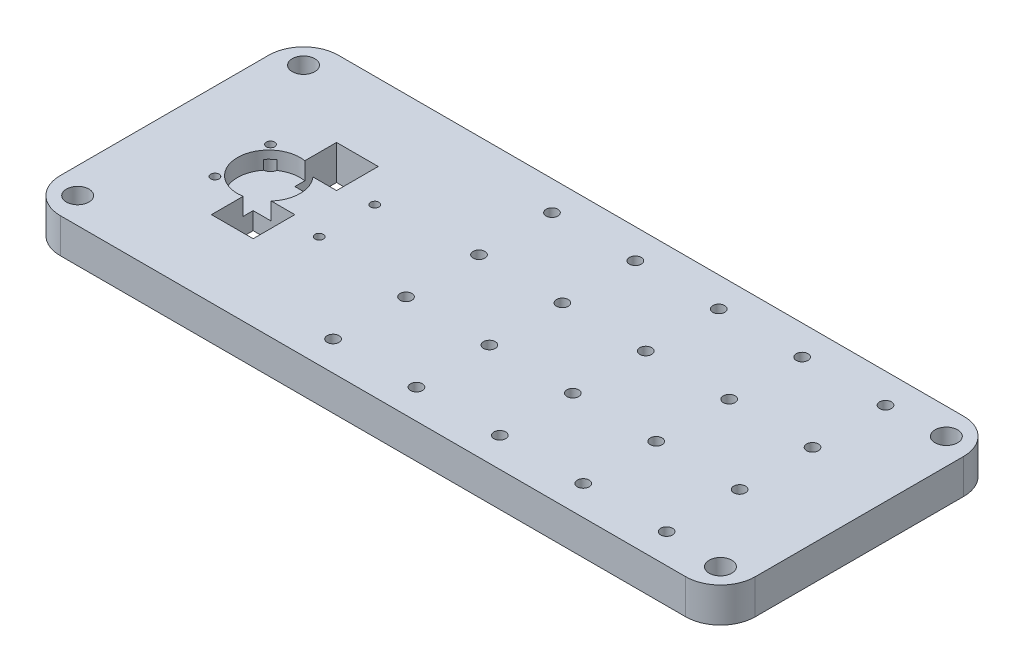
SolidWorks part; units mm, degrees
ref_plane "前视基准面" through (0, 0, 0) normal (0, 0, 1) x (1, 0, 0)
ref_plane "上视基准面" through (0, 0, 0) normal (0, 1, 0) x (1, 0, 0)
ref_plane "右视基准面" through (0, 0, 0) normal (1, 0, 0) x (0, 0, -1)
other "Configuration Table"
sketch "草图1" plane through (0, 0, 0) normal (0, 1, 0) x (1, 0, 0)
  line L1 (-100, 40) -> (100, 40)
  line L2 (-100, 40) -> (-100, -40)
  line L3 (-100, -40) -> (100, -40)
  line L4 (100, 40) -> (100, -40)
  line L5 (-100, 40) -> (100, -40) construction
  line L6 (-100, -40) -> (100, 40) construction
  point P0 (0, 0)
  dimension "D1" = 200
  dimension "D2" = 80
extrude "凸台-拉伸1" add sketch "草图1" along normal blind 10
sketch "草图3" plane through (0, 10, 0) normal (0, 1, 0) x (1, 0, 0)
  circle A0 centre (-70, 0) radius 9
  dimension "D1" = 18
  dimension "D2" = 70
extrude "切除-拉伸1" cut sketch "草图3" against normal blind 5
sketch "草图4" plane through (0, 0, 0) normal (0, -1, 0) x (1, 0, 0)
  line L0 (0, 0) -> (-107.4442, 0) construction
  circle A0 centre (-70, 0) radius 9 construction
  point P3 (-77.5, 8)
  point P4 (-47.5, 8)
  point P5 (-47.5, -8)
  point P6 (-77.5, -8)
  dimension "D3" = 7.5
  dimension "D1" = 30
  dimension "D2" = 16
hole_wizard "M2 六角凹头螺钉的柱形沉头孔1" positions "草图7" profile "草图6" counterbore size "M2" standard "ISO" end condition through all
sketch "草图7" plane through (0, 0, 0) normal (0, -1, 0) x (-1, 0, 0)
  point P0 (47.5, 8)
  point P3 (77.5, 8)
  point P6 (77.5, -8)
  point P9 (47.5, -8)
sketch "草图6" plane through (-47.5, 0, -8) normal (1, 0, 0) x (0, 0, -1)
  line L0 (0, 0) -> (0, 10)
  line L1 (0, 10) -> (1.2, 10)
  line L3 (1.2, 10) -> (1.2, 7.7)
  line L4 (1.2, 7.7) -> (2.5, 7.7)
  line L5 (2.5, 7.7) -> (2.5, 0)
  line L7 (2.5, 0) -> (0, 0)
  line L11 (0, -6.35) -> (0, 107.95) construction
  dimension "通孔孔直径" = 2.4
  dimension "通孔孔深度" = 10
  dimension "柱形沉头孔直径" = 5
  dimension "柱形沉头孔深度" = 7.7
sketch "草图8" plane through (0, 10, 0) normal (0, 1, 0) x (1, 0, 0)
  line L0 (-77.5, 8) -> (-47.5, -8) construction
  line L1 (-77.5, -8) -> (-47.5, 8) construction
  line L2 (-81.75, 12.25) -> (-43.25, 12.25) construction
  line L3 (-79.75, 10.25) -> (-45.25, 10.25)
  line L4 (-79.75, 10.25) -> (-79.75, -10.25)
  line L5 (-79.75, -10.25) -> (-45.25, -10.25)
  line L6 (-45.25, 10.25) -> (-45.25, -10.25)
  line L7 (-79.75, 10.25) -> (-45.25, -10.25) construction
  line L8 (-79.75, -10.25) -> (-45.25, 10.25) construction
  line L9 (-43.25, 12.25) -> (-43.25, -12.25) construction
  line L10 (-81.75, -12.25) -> (-43.25, -12.25) construction
  line L11 (-81.75, 12.25) -> (-81.75, -12.25) construction
  point P8 (-62.5, 0)
  dimension "D1" = 20.5
  dimension "D2" = 34.5
  dimension "D3" = 2
ref_plane "基准面1" through (0, 25, 0) normal (0, 1, 0) x (1, 0, 0)
sketch "草图11" plane through (0, 10, 0) normal (0, 1, 0) x (1, 0, 0)
  line L0 (-81.75, 12.25) -> (-81.75, -12.25) construction
  line L1 (-81.75, -12.25) -> (-43.25, -12.25) construction
  line L2 (-43.25, 12.25) -> (-43.25, -12.25) construction
  line L3 (-81.75, 12.25) -> (-43.25, 12.25) construction
  line L4 (-81.75, 12.25) -> (-81.75, -12.25) construction
  line L5 (-81.75, -12.25) -> (-43.25, -12.25) construction
  line L6 (-43.25, 12.25) -> (-43.25, -12.25) construction
  line L7 (-81.75, 12.25) -> (-43.25, 12.25) construction
  line L8 (-91.75, 22.25) -> (-91.75, -22.25)
  line L9 (-91.75, -22.25) -> (-33.25, -22.25)
  line L10 (-33.25, 22.25) -> (-33.25, -22.25)
  line L11 (-91.75, 22.25) -> (-33.25, 22.25)
  dimension "D1" = 10
sketch "草图12" plane through (0, 25, 0) normal (0, 1, 0) x (1, 0, 0)
  line L0 (-81.75, 12.25) -> (-81.75, -12.25) construction
  line L1 (-81.75, -12.25) -> (-43.25, -12.25) construction
  line L2 (-43.25, 12.25) -> (-43.25, -12.25) construction
  line L3 (-81.75, 12.25) -> (-43.25, 12.25) construction
  line L4 (-81.75, 12.25) -> (-81.75, -12.25)
  line L5 (-81.75, -12.25) -> (-43.25, -12.25)
  line L6 (-43.25, 12.25) -> (-43.25, -12.25)
  line L7 (-81.75, 12.25) -> (-43.25, 12.25)
sketch "草图13" plane through (0, 10, 0) normal (0, 1, 0) x (1, 0, 0)
  line L0 (0, 0) -> (-107.4442, 0) construction
  line L3 (-100, 40) -> (-100, -40) construction
  circle A27 centre (-20, 31.5) radius 1.7
  circle A29 centre (4, 31.5) radius 1.7
  circle A30 centre (28, 31.5) radius 1.7
  circle A31 centre (52, 31.5) radius 1.7
  circle A32 centre (76, 31.5) radius 1.7
  circle A33 centre (4, 10.5) radius 1.7
  circle A34 centre (28, 10.5) radius 1.7
  circle A35 centre (52, 10.5) radius 1.7
  circle A36 centre (76, 10.5) radius 1.7
  circle A37 centre (4, -10.5) radius 1.7
  circle A38 centre (28, -10.5) radius 1.7
  circle A39 centre (52, -10.5) radius 1.7
  circle A40 centre (76, -10.5) radius 1.7
  circle A41 centre (4, -31.5) radius 1.7
  circle A42 centre (28, -31.5) radius 1.7
  circle A43 centre (52, -31.5) radius 1.7
  circle A44 centre (76, -31.5) radius 1.7
  circle A69 centre (-20, 10.5) radius 1.7
  circle A70 centre (-20, -10.5) radius 1.7
  circle A71 centre (-20, -31.5) radius 1.7
  dimension "D1" = 31.5
  dimension "D3" = 3.4
  dimension "D2" = 80
  dimension "D6" = 24
  dimension "D7" = 21
  dimension "D5" = 5
  dimension "D4" = 4
extrude "切除-拉伸3" cut sketch "草图13" against normal through all
sketch "草图14" plane through (0, 10, 0) normal (0, 1, 0) x (1, 0, 0)
  line L0 (0, 40) -> (0, -40) construction
  line L1 (100, 40) -> (-100, 40) construction
  line L2 (-100, -40) -> (100, -40) construction
  line L3 (-100, 0) -> (100, 0) construction
  line L4 (-100, 40) -> (-100, -40) construction
  line L5 (100, -40) -> (100, 40) construction
  circle A0 centre (-92.5, 32.5) radius 3.25
  circle A1 centre (92.5, 32.5) radius 3.25
  circle A2 centre (92.5, -32.5) radius 3.25
  circle A3 centre (-92.5, -32.5) radius 3.25
  dimension "D1" = 6.5
  dimension "D2" = 185
  dimension "D3" = 65
extrude "切除-拉伸4" cut sketch "草图14" against normal through all
fillet "Fillet1" radius 10 4 edges at (100, 5, -40) (100, 5, 40) (-100, 5, 40) (-100, 5, -40)
sketch "Sketch3" plane through (0, 10, 0) normal (0, 1, 0) x (1, 0, 0)
  line L0 (-79.75, -10.25) -> (-45.25, -10.25) construction
  line L1 (-68.5, -18) -> (-56.5, -18)
  line L2 (-68.5, -18) -> (-68.5, -6)
  line L3 (-68.5, -6) -> (-56.5, -6)
  line L4 (-56.5, -18) -> (-56.5, -6)
  line L6 (-56.5, 18) -> (-68.5, 18)
  line L7 (-56.5, 18) -> (-56.5, 6)
  line L8 (-56.5, 6) -> (-68.5, 6)
  line L9 (-68.5, 18) -> (-68.5, 6)
  line L10 (-62.5, 6) -> (-62.5, -6) construction
  point P12 (-62.5, 6)
  point P13 (-62.5, -6)
  point P14 (-62.5, -10.25)
  point P15 (-62.5, 0)
  dimension "D1" = 12
  dimension "D2" = 12
  dimension "D3" = 12
extrude "Cut-Extrude2" cut sketch "Sketch3" against normal through all
